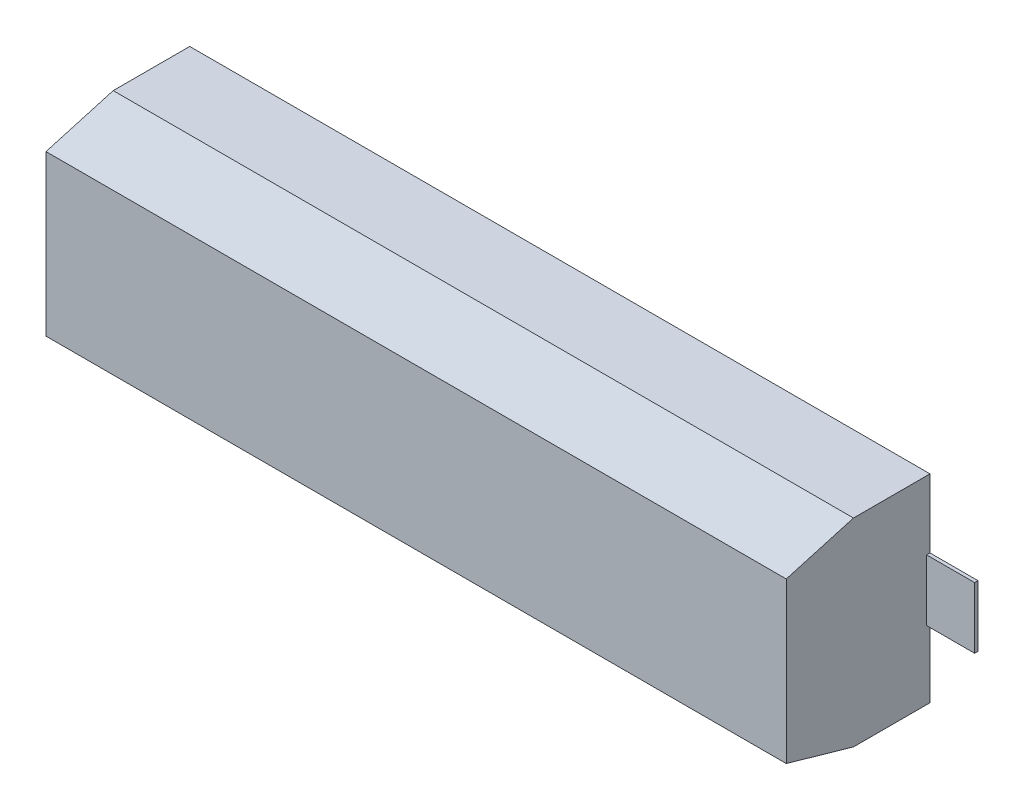
SolidWorks part; units mm, degrees
ref_plane "Front Plane" through (0, 0, 0) normal (0, 0, 1) x (1, 0, 0)
ref_plane "Top Plane" through (0, 0, 0) normal (0, 1, 0) x (1, 0, 0)
ref_plane "Right Plane" through (0, 0, 0) normal (1, 0, 0) x (0, 0, -1)
sketch "Sketch1" plane through (0, 0, 0) normal (0, 0, 1) x (1, 0, 0)
  line L1 (-38.555, 10.325) -> (38.555, 10.325)
  line L2 (-38.555, 10.325) -> (-38.555, -10.325)
  line L3 (-38.555, -10.325) -> (38.555, -10.325)
  line L4 (38.555, 10.325) -> (38.555, -10.325)
  line L5 (-38.555, 10.325) -> (38.555, -10.325) construction
  line L6 (-38.555, -10.325) -> (38.555, 10.325) construction
  point P0 (0, 0)
  point P6 (0, 0)
  dimension "D1" = 77.11
  dimension "D2" = 20.65
extrude "Boss-Extrude1" add sketch "Sketch1" along normal blind 14.97
chamfer "Chamfer1" distance 7 distance2 2 2 edges at (0, -10.325, 14.97) (0, 10.325, 14.97)
sketch "Sketch2" plane through (0, 0, 0) normal (0, 0, -1) x (-1, 0, 0)
  line L0 (-38.555, -10.325) -> (-38.555, 10.325) construction
  line L1 (-38.555, 3.19) -> (-43.555, 3.19)
  line L2 (-38.555, 3.19) -> (-38.555, -3.19)
  line L3 (-38.555, -3.19) -> (-43.555, -3.19)
  line L4 (-43.555, 3.19) -> (-43.555, -3.19)
  line L12 (-43.555, 0) -> (-38.555, 0) construction
  line L13 (0, 9.2318) -> (0, -7.0057) construction
  line L14 (38.555, -3.19) -> (43.555, -3.19)
  line L15 (43.555, 3.19) -> (43.555, -3.19)
  line L16 (38.555, 3.19) -> (43.555, 3.19)
  line L17 (38.555, 3.19) -> (38.555, -3.19)
  dimension "D1" = 6.38
  dimension "D2" = 5
extrude "Boss-Extrude2" add sketch "Sketch2" against normal blind 0.35
